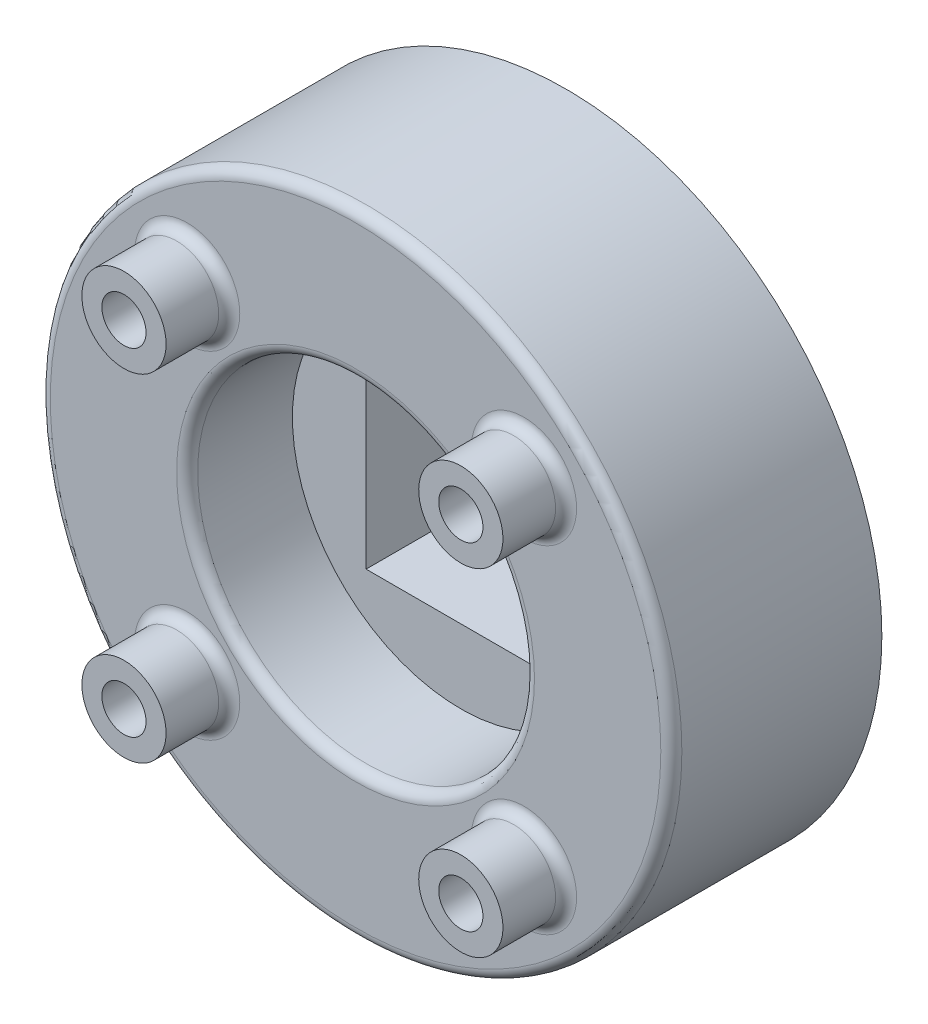
SolidWorks part; units mm, degrees
material "Copper"
ref_plane "Front Plane" through (0, 0, 0) normal (0, 0, 1) x (1, 0, 0)
ref_plane "Top Plane" through (0, 0, 0) normal (0, 1, 0) x (1, 0, 0)
ref_plane "Right Plane" through (0, 0, 0) normal (1, 0, 0) x (0, 0, -1)
sketch "Sketch2" plane through (0, 0, 0) normal (0, 0, 1) x (1, 0, 0)
  circle A0 centre (0, 0) radius 75
extrude "Base Extrude" add sketch "Sketch2" along normal blind 50
sketch "Sketch3" plane through (0, 0, 50) normal (0, 0, 1) x (1, 0, 0)
  circle A0 centre (0, 0) radius 40
extrude "Circular Cut" cut sketch "Sketch3" against normal blind 25
sketch "Sketch5" plane through (0, 0, 25) normal (0, 0, 1) x (1, 0, 0)
  line L1 (22.5, -22.5) -> (-22.5, -22.5)
  line L2 (22.5, -22.5) -> (22.5, 22.5)
  line L3 (22.5, 22.5) -> (-22.5, 22.5)
  line L4 (-22.5, -22.5) -> (-22.5, 22.5)
  line L5 (22.5, -22.5) -> (-22.5, 22.5) construction
  line L6 (22.5, 22.5) -> (-22.5, -22.5) construction
  point P0 (0, 0)
  dimension "D1" = 45
  dimension "D2" = 45
extrude "Square Cut" cut sketch "Sketch5" against normal through all
sketch "Sketch6" plane through (0, 0, 50) normal (0, 0, 1) x (1, 0, 0)
  line L0 (-75, 0) -> (75, 0) construction
  line L1 (0, 75) -> (0, -75) construction
  circle A0 centre (0, 0) radius 75 construction
  circle A1 centre (-40, 40) radius 10
  point P7 (-40, 40)
  point P8 (40, 40)
  point P9 (40, -40)
  point P10 (-40, -40)
  point P11 (-40, 40)
extrude "Circular Tower" add sketch "Sketch6" along normal blind 15
fillet "Fillet 1" radius 2.5 1 edges at (-30, 40, 50)
sketch "Sketch" plane through (0, 0, 65) normal (0, 0, 1) x (1, 0, 0)
  point P0 (-40, 40)
hole_wizard "M12x1.5 Tapped Hole" positions "3DSketch1" profile "Sketch8" tap size "M12x1.5" standard "ANSI Metric"
sketch3d "3DSketch1"
  point P0 (-40, 40, 65)
sketch "Sketch8" plane through (-40, 40, 65) normal (1, 0, 0) x (0, -1, 0)
  line L0 (0, 0) -> (0, 34.6545)
  line L1 (0, 34.6545) -> (5.25, 31.5)
  line L2 (5.25, 31.5) -> (5.25, 0)
  line L5 (5.25, 0) -> (0, 0)
  line L10 (0, 34.6545) -> (-5.25, 31.5) construction
  line L11 (0, -6.35) -> (0, 107.95) construction
  dimension "Tap Drill Dia." = 10.5
  dimension "Tap Drill Depth" = 31.5
  dimension "Drill Angle" = 118
cosmetic thread "Hole Thread1" parameters "D1"=24, "D2"=12
pattern_circular "CirPattern" count 4 over 360 about axis through (0, 0, 0) along (0, 0, 1) of "Circular Tower", "Fillet 1", "M12x1.5 Tapped Hole"
fillet "Fillet 2" radius 2.5 2 edges at (40, 0, 50) (75, 0, 50)
